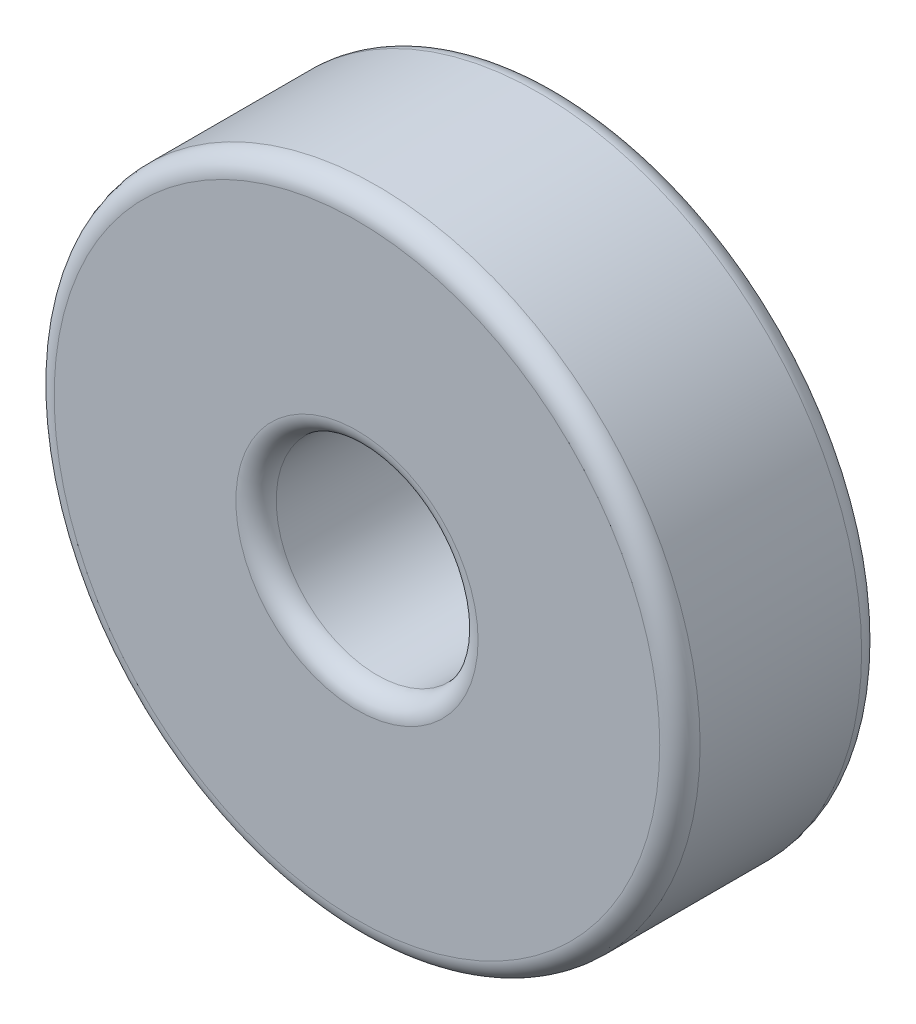
SolidWorks part; units mm, degrees
ref_plane "Alzado" through (0, 0, 0) normal (0, 0, 1) x (1, 0, 0)
ref_plane "Planta" through (0, 0, 0) normal (0, 1, 0) x (1, 0, 0)
ref_plane "Vista lateral" through (0, 0, 0) normal (1, 0, 0) x (0, 0, -1)
sketch "Croquis1" plane through (0, 0, 0) normal (0, 0, 1) x (1, 0, 0)
  circle A0 centre (0, 0) radius 2.5
  circle A1 centre (0, 0) radius 8
  dimension "D1" = 16
  dimension "D2" = 5
extrude "Saliente-Extruir1" add sketch "Croquis1" along normal blind 5
fillet "Redondeo1" radius 0.5 4 edges at (2.5, 0, 0) (8, 0, 0) (2.5, 0, 5) (8, 0, 5)
